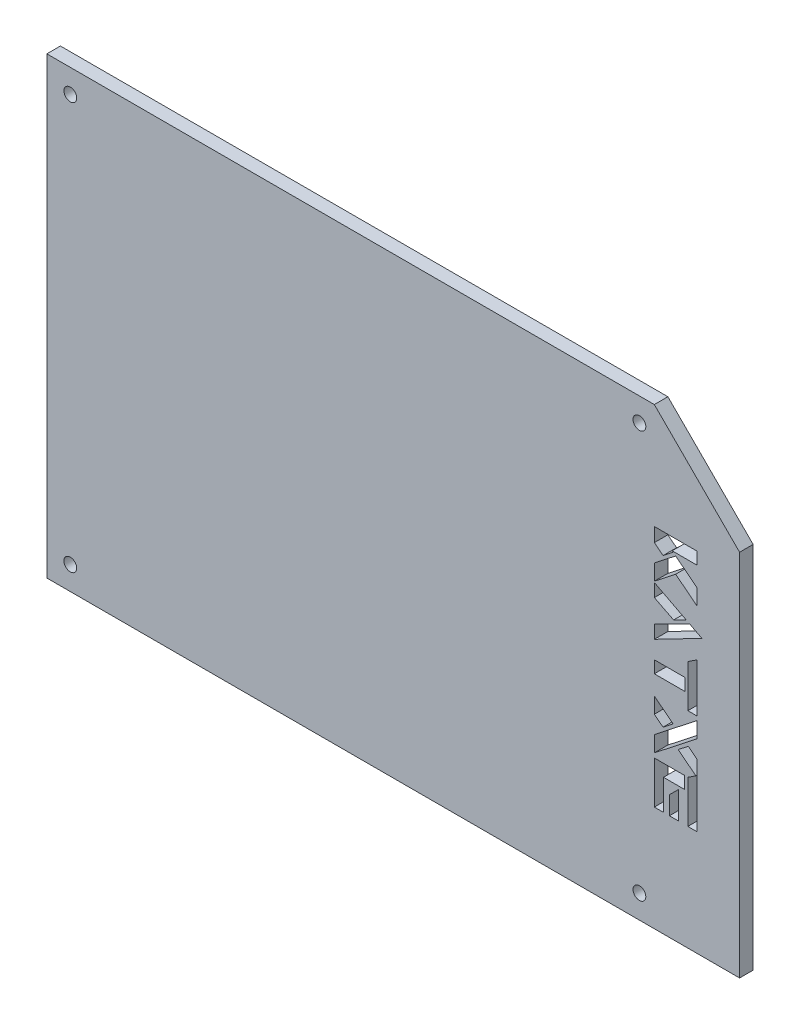
SolidWorks part; units mm, degrees
ref_plane "Front Plane" through (0, 0, 0) normal (0, 0, 1) x (1, 0, 0)
ref_plane "Top Plane" through (0, 0, 0) normal (0, 1, 0) x (1, 0, 0)
ref_plane "Right Plane" through (0, 0, 0) normal (1, 0, 0) x (0, 0, -1)
sketch "Sketch1" plane through (0, 0, 0) normal (0, 0, 1) x (1, 0, 0)
  line L1 (70.25, 53.25) -> (-70.25, 53.25)
  line L2 (70.25, 53.25) -> (70.25, -53.25)
  line L3 (70.25, -53.25) -> (-70.25, -53.25)
  line L4 (-70.25, 53.25) -> (-70.25, -53.25)
  line L5 (70.25, 53.25) -> (-70.25, -53.25) construction
  line L6 (70.25, -53.25) -> (-70.25, 53.25) construction
  line L8 (70.25, 53.25) -> (-72.25, 53.25) construction
  line L9 (-70.25, 53.25) -> (-72.25, 53.25)
  line L10 (-70.25, 53.25) -> (-70.25, -53.25)
  line L11 (-70.25, -53.25) -> (-72.25, -53.25)
  line L12 (-72.25, 53.25) -> (-72.25, -53.25)
  circle A0 centre (66.75, 47.75) radius 1.5 construction
  circle A1 centre (-66.75, 47.75) radius 1.5 construction
  circle A2 centre (66.75, -47.75) radius 1.5 construction
  circle A3 centre (-66.75, -47.75) radius 1.5 construction
  circle A4 centre (66.75, 47.75) radius 1.5
  circle A5 centre (-66.75, 47.75) radius 1.5
  circle A6 centre (66.75, -47.75) radius 1.5
  circle A7 centre (-66.75, -47.75) radius 1.5
  point P0 (0, 0)
  dimension "D3" = 2
extrude "Boss-Extrude1" add sketch "Sketch1" along normal blind 3.175 contours L1 L4 L3 L2 A7 A6 A5 A4 | L9 L12 L11 L4
sketch "Sketch2" plane through (0, 0, 0) normal (0, 0, 1) x (1, 0, 0)
  line L2 (70.25, 53.25) -> (90.25, 33.25)
  line L3 (90.25, 33.25) -> (90.25, -53.25)
  line L4 (90.25, -53.25) -> (70.25, -53.25)
  line L5 (70.25, 53.25) -> (70.25, -53.25) construction
  line L6 (70.25, 53.25) -> (70.25, -53.25)
  dimension "D1" = 20
  dimension "D2" = 135
extrude "Boss-Extrude2" add sketch "Sketch2" along normal up to surface (3.175 mm away) up to face at (-65.25, -47.75, 3.175)
sketch "Sketch3" plane through (0, 0, 3.175) normal (0, 0, 1) x (1, 0, 0)
  line L0 (70.25, 53.25) -> (70.25, -53.25) construction
  line L2 (90.25, -53.25) -> (-72.25, -53.25) construction
  text T0 "KATXE" font "Revamped" height 10
extrude "Cut-Extrude1" cut sketch "Sketch3" against normal up to surface (3.175 mm away) up to face at (-65.25, -47.75, 0)
sketch "Sketch4" plane through (0, 0, 3.175) normal (0, 0, 1) x (1, 0, 0)
  line L4 (75.9257, -22.1136) -> (73.7825, -24.2525)
  line L5 (75.9257, -28.5283) -> (75.9257, -22.1136)
  line L6 (73.7825, -28.5283) -> (75.9257, -28.5283)
  line L7 (73.7825, -24.2525) -> (73.7825, -28.5283)
  line L8 (75.9257, -22.1136) -> (73.7825, -24.2525)
  line L9 (75.9257, -28.5283) -> (75.9257, -22.1136)
  line L10 (73.7825, -28.5283) -> (75.9257, -28.5283)
  line L11 (73.7825, -24.2525) -> (73.7825, -28.5283)
  line L12 (70.25, -1.4506) -> (77.4122, -1.4506)
  line L13 (70.25, 1.3999) -> (70.25, -1.4506)
  line L14 (77.4122, 1.3999) -> (70.25, 1.3999)
  line L15 (77.4122, -1.4506) -> (77.4122, 1.3999)
  line L16 (70.25, -1.4506) -> (77.4122, -1.4506)
  line L17 (70.25, 1.3999) -> (70.25, -1.4506)
  line L18 (77.4122, 1.3999) -> (70.25, 1.3999)
  line L19 (77.4122, -1.4506) -> (77.4122, 1.3999)
  line L20 (80.25, -5.9607) -> (70.25, -13.8007)
  line L21 (80.25, -9.6664) -> (80.25, -5.9607)
  line L22 (70.25, -17.5063) -> (80.25, -9.6664)
  line L23 (78.2082, -12.1959) -> (75.8433, -14.0498)
  line L24 (80.25, -13.8007) -> (78.2082, -12.1959)
  line L25 (80.25, -28.5283) -> (80.25, -13.8007)
  line L26 (78.1068, -28.5283) -> (80.25, -28.5283)
  line L27 (78.1068, -18.5515) -> (78.1068, -28.5283)
  line L28 (79.9878, -17.3007) -> (78.1068, -18.5515)
  line L29 (75.8433, -14.0498) -> (79.9878, -17.3007)
  line L30 (78.2082, -12.1959) -> (75.8433, -14.0498)
  line L31 (80.25, -13.8007) -> (78.2082, -12.1959)
  line L32 (80.25, -28.5283) -> (80.25, -13.8007)
  line L33 (78.1068, -28.5283) -> (80.25, -28.5283)
  line L34 (78.1068, -18.5515) -> (78.1068, -28.5283)
  line L35 (79.9878, -17.3007) -> (78.1068, -18.5515)
  line L36 (75.8433, -14.0498) -> (79.9878, -17.3007)
  line L37 (70.25, -13.8007) -> (70.25, -17.5063)
  line L38 (80.25, -5.9607) -> (70.25, -13.8007)
  line L39 (80.25, -9.6664) -> (80.25, -5.9607)
  line L40 (70.25, -17.5063) -> (80.25, -9.6664)
  line L41 (70.25, -13.8007) -> (70.25, -17.5063)
  line L42 (80.25, 6.3872) -> (78.1068, 4.962)
  line L43 (80.25, -5.0148) -> (80.25, 6.3872)
  line L44 (70.25, -28.5283) -> (72.3932, -28.5283)
  line L45 (70.25, -18.5515) -> (70.25, -28.5283)
  line L46 (77.3763, -18.5515) -> (70.25, -18.5515)
  line L47 (77.3763, -21.402) -> (77.3763, -18.5515)
  line L48 (72.3932, -21.402) -> (77.3763, -21.402)
  line L49 (72.3932, -28.5283) -> (72.3932, -21.402)
  line L50 (70.25, -28.5283) -> (72.3932, -28.5283)
  line L51 (70.25, -18.5515) -> (70.25, -28.5283)
  line L52 (77.3763, -18.5515) -> (70.25, -18.5515)
  line L53 (77.3763, -21.402) -> (77.3763, -18.5515)
  line L54 (72.3932, -21.402) -> (77.3763, -21.402)
  line L55 (72.3932, -28.5283) -> (72.3932, -21.402)
  line L56 (78.1068, -5.0148) -> (80.25, -5.0148)
  line L57 (78.1068, 4.962) -> (78.1068, -5.0148)
  line L58 (80.25, 6.3872) -> (78.1068, 4.962)
  line L59 (80.25, -5.0148) -> (80.25, 6.3872)
  line L60 (78.1068, -5.0148) -> (80.25, -5.0148)
  line L61 (78.1068, 4.962) -> (78.1068, -5.0148)
  line L62 (70.25, 17.0988) -> (70.25, 14.0329)
  line L63 (77.7204, 13.2348) -> (70.25, 17.0988)
  line L64 (74.7644, 11.7462) -> (77.7204, 13.2348)
  line L65 (70.25, 14.0329) -> (74.7644, 11.7462)
  line L66 (70.25, 17.0988) -> (70.25, 14.0329)
  line L67 (77.7204, 13.2348) -> (70.25, 17.0988)
  line L68 (74.7644, 11.7462) -> (77.7204, 13.2348)
  line L69 (70.25, 14.0329) -> (74.7644, 11.7462)
  line L70 (70.25, 5.5532) -> (81.4134, 11.326)
  line L71 (70.25, 8.617) -> (70.25, 5.5532)
  line L72 (78.5629, 12.8019) -> (70.25, 8.617)
  line L73 (81.4134, 11.326) -> (78.5629, 12.8019)
  line L74 (70.25, 5.5532) -> (81.4134, 11.326)
  line L75 (70.25, 8.617) -> (70.25, 5.5532)
  line L76 (78.5629, 12.8019) -> (70.25, 8.617)
  line L77 (81.4134, 11.326) -> (78.5629, 12.8019)
  line L78 (70.25, -5.9607) -> (70.25, -9.6664)
  line L79 (74.6546, -9.4172) -> (70.25, -5.9607)
  line L80 (72.2918, -11.269) -> (74.6546, -9.4172)
  line L81 (70.25, 25.1985) -> (72.2918, 23.5959)
  line L82 (70.25, 28.4755) -> (70.25, 25.1985)
  line L83 (80.25, 28.4755) -> (70.25, 28.4755)
  line L84 (80.25, 25.625) -> (80.25, 28.4755)
  line L85 (74.4265, 25.625) -> (80.25, 25.625)
  line L86 (74.6546, 25.4476) -> (74.4265, 25.625)
  line L87 (72.2918, 23.5959) -> (74.6546, 25.4476)
  line L88 (70.25, 25.1985) -> (72.2918, 23.5959)
  line L89 (70.25, 28.4755) -> (70.25, 25.1985)
  line L90 (80.25, 28.4755) -> (70.25, 28.4755)
  line L91 (80.25, 25.625) -> (80.25, 28.4755)
  line L92 (74.4265, 25.625) -> (80.25, 25.625)
  line L93 (74.6546, 25.4476) -> (74.4265, 25.625)
  line L94 (72.2918, 23.5959) -> (74.6546, 25.4476)
  line L95 (70.25, -9.6664) -> (72.2918, -11.269)
  line L96 (70.25, -5.9607) -> (70.25, -9.6664)
  line L97 (74.6546, -9.4172) -> (70.25, -5.9607)
  line L98 (72.2918, -11.269) -> (74.6546, -9.4172)
  line L99 (70.25, -9.6664) -> (72.2918, -11.269)
  line L101 (70.25, 53.25) -> (-72.25, 53.25)
  line L102 (80.25, 21.0642) -> (75.25, 24.9852)
  line L103 (80.25, 17.3585) -> (80.25, 21.0642)
  line L104 (75.25, 21.2796) -> (80.25, 17.3585)
  line L105 (70.25, 17.3585) -> (75.25, 21.2796)
  line L106 (70.25, 21.0642) -> (70.25, 17.3585)
  line L107 (75.25, 24.9852) -> (70.25, 21.0642)
  line L108 (80.25, 21.0642) -> (75.25, 24.9852)
  line L109 (80.25, 17.3585) -> (80.25, 21.0642)
  line L110 (75.25, 21.2796) -> (80.25, 17.3585)
  line L111 (70.25, 17.3585) -> (75.25, 21.2796)
  line L112 (70.25, 21.0642) -> (70.25, 17.3585)
  line L113 (75.25, 24.9852) -> (70.25, 21.0642)
  line L114 (-72.25, 53.25) -> (-72.25, -53.25)
  line L115 (-72.25, -53.25) -> (90.25, -53.25)
  line L116 (90.25, -53.25) -> (90.25, 33.25)
  line L117 (90.25, 33.25) -> (70.25, 53.25)
  line L118 (70.25, 53.25) -> (-72.25, 53.25)
  line L119 (-72.25, 53.25) -> (-72.25, -53.25)
  line L120 (-72.25, -53.25) -> (90.25, -53.25)
  line L121 (90.25, -53.25) -> (90.25, 33.25)
  line L122 (90.25, 33.25) -> (70.25, 53.25)
  circle A1 centre (-66.75, -47.75) radius 1.5
  circle A2 centre (-66.75, -47.75) radius 1.5
  circle A3 centre (66.75, -47.75) radius 1.5
  circle A4 centre (66.75, -47.75) radius 1.5
  circle A5 centre (-66.75, 47.75) radius 1.5
  circle A6 centre (-66.75, 47.75) radius 1.5
  circle A7 centre (66.75, 47.75) radius 1.5
  circle A8 centre (66.75, 47.75) radius 1.5
  dimension "D17" = 162.5
  dimension "D18" = 106.5
  dimension "D1" = 0
  dimension "D2" = 0
  dimension "D3" = 0
  dimension "D4" = 0
  dimension "D5" = 0
  dimension "D6" = 0
  dimension "D7" = 0
  dimension "D8" = 0
  dimension "D9" = 0
  dimension "D10" = 0
  dimension "D11" = 0
  dimension "D12" = 0
  dimension "D13" = 0
  dimension "D14" = 0
  dimension "D15" = 0
  dimension "D16" = 0
